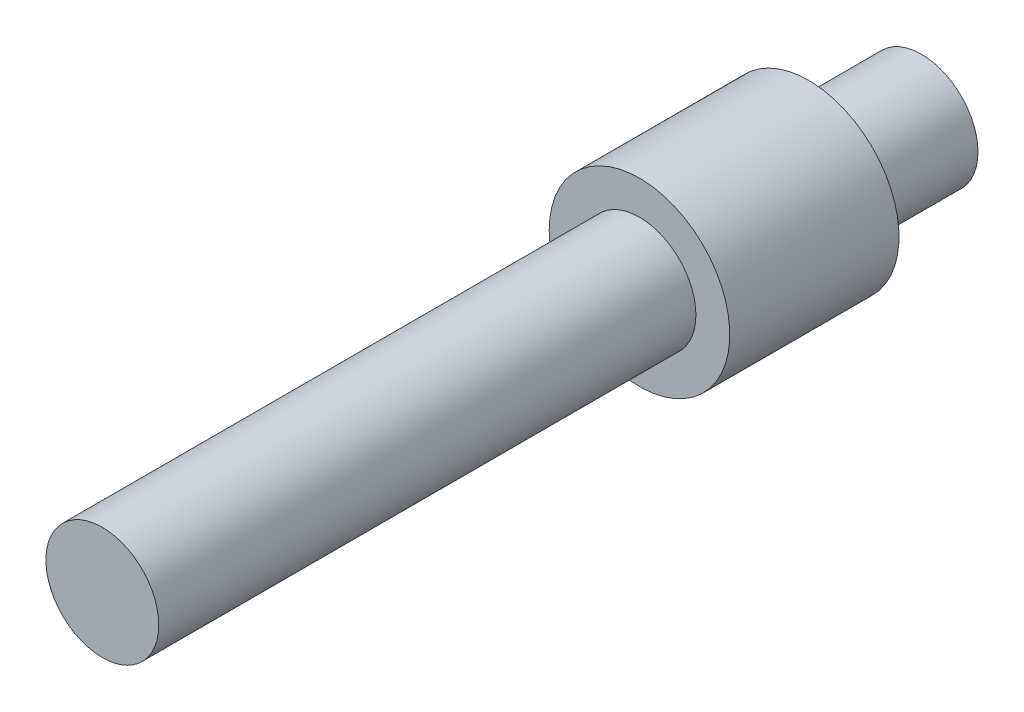
SolidWorks part; units mm, degrees
ref_plane "Front Plane" through (0, 0, 0) normal (0, 0, 1) x (1, 0, 0)
ref_plane "Top Plane" through (0, 0, 0) normal (0, 1, 0) x (1, 0, 0)
ref_plane "Right Plane" through (0, 0, 0) normal (1, 0, 0) x (0, 0, -1)
sketch "Sketch1" plane through (0, 0, 0) normal (0, 0, 1) x (1, 0, 0)
  circle A0 centre (0, 0) radius 6.35
  dimension "D1" = 12.7
extrude "Boss-Extrude1" add sketch "Sketch1" against normal blind 92.202
sketch "Sketch2" plane through (0, 0, -92.202) normal (0, 0, -1) x (-1, 0, 0)
  circle A0 centre (0, 0) radius 10.16
  dimension "D1" = 20.32
extrude "Boss-Extrude2" add sketch "Sketch2" against normal blind 19.05 from offset 12.7 contours A0
